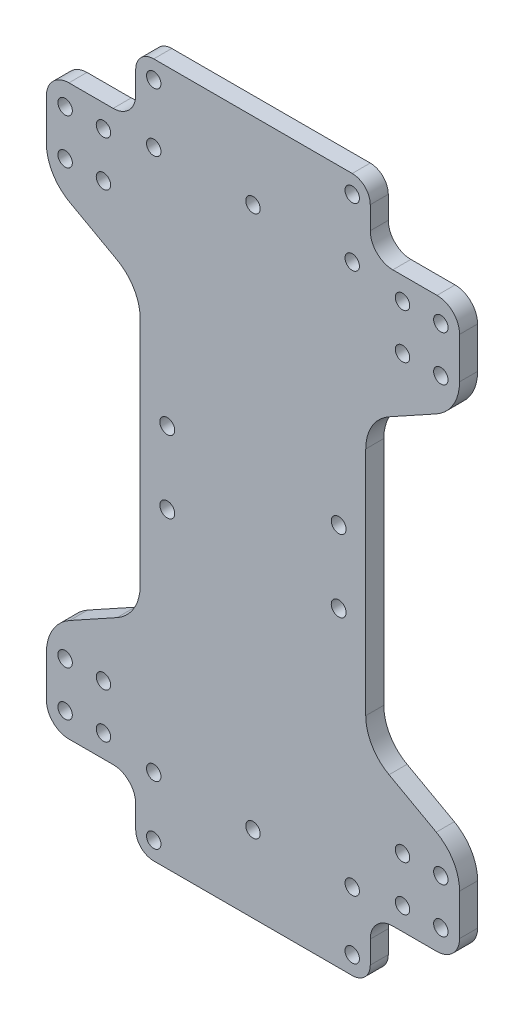
SolidWorks part; units mm, degrees
material "Acrylic (Medium-high impact)"
ref_plane "Front Plane" through (0, 0, 0) normal (0, 0, 1) x (1, 0, 0)
ref_plane "Top Plane" through (0, 0, 0) normal (0, 1, 0) x (1, 0, 0)
ref_plane "Right Plane" through (0, 0, 0) normal (1, 0, 0) x (0, 0, -1)
sketch "Sketch1" plane through (0, 0, 0) normal (0, 0, 1) x (1, 0, 0)
  line L0 (1.25, 62.9364) -> (93.1655, 62.9364) construction
  line L1 (1.4077, -0.0636) -> (16.2069, -0.0636)
  line L2 (1.4077, -0.0636) -> (1.4077, 19.9364)
  line L3 (69.2085, 2.9364) -> (69.2085, -10.0636) construction
  line L4 (80.3577, 4.9364) -> (80.3577, 14.9364) construction
  line L5 (1.4077, 19.9364) -> (22.2077, 31.43)
  line L6 (25.2069, 2.9364) -> (47.2077, 2.9364) construction
  line L7 (88.8577, 14.9364) -> (80.3577, 14.9364) construction
  line L8 (47.2077, -14.0636) -> (47.2077, 139.9364) construction
  line L9 (88.8577, 4.9364) -> (88.8577, 14.9364) construction
  line L10 (21.2069, -5.0636) -> (21.2069, -10.0636)
  line L11 (22.2077, 94.4428) -> (22.2077, 31.43)
  line L12 (88.8577, 4.9364) -> (80.3577, 4.9364) construction
  line L13 (80.3577, 9.9364) -> (88.8577, 9.9364) construction
  line L14 (14.0577, 9.9364) -> (5.5577, 9.9364) construction
  line L15 (5.5577, 4.9364) -> (14.0577, 4.9364) construction
  line L16 (5.5577, 4.9364) -> (5.5577, 14.9364) construction
  line L17 (5.5577, 14.9364) -> (14.0577, 14.9364) construction
  line L18 (14.0577, 4.9364) -> (14.0577, 14.9364) construction
  line L19 (72.2077, 94.4428) -> (72.2077, 31.43)
  line L20 (73.2085, -5.0636) -> (73.2085, -10.0636)
  line L21 (93.0077, 19.9364) -> (72.2077, 31.43)
  line L22 (93.0077, -0.0636) -> (93.0077, 19.9364)
  line L23 (93.0077, -0.0636) -> (78.2085, -0.0636)
  line L24 (25.2069, 122.9364) -> (25.2069, 135.9364) construction
  line L25 (14.0577, 120.9364) -> (14.0577, 110.9364) construction
  line L26 (5.5577, 110.9364) -> (14.0577, 110.9364) construction
  line L27 (5.5577, 120.9364) -> (5.5577, 110.9364) construction
  line L28 (5.5577, 120.9364) -> (14.0577, 120.9364) construction
  line L29 (14.0577, 115.9364) -> (5.5577, 115.9364) construction
  line L30 (80.3577, 115.9364) -> (88.8577, 115.9364) construction
  line L31 (88.8577, 120.9364) -> (80.3577, 120.9364) construction
  line L32 (88.8577, 120.9364) -> (88.8577, 110.9364) construction
  line L33 (88.8577, 110.9364) -> (80.3577, 110.9364) construction
  line L34 (25.2069, 122.9364) -> (47.2077, 122.9364) construction
  line L35 (25.2069, -14.0636) -> (69.2085, -14.0636)
  line L36 (80.3577, 120.9364) -> (80.3577, 110.9364) construction
  line L37 (69.2085, 122.9364) -> (69.2085, 135.9364) construction
  line L38 (25.2069, 2.9364) -> (25.2069, -10.0636) construction
  line L39 (25.2069, 139.9364) -> (69.2085, 139.9364)
  line L40 (93.0077, 125.9364) -> (78.2085, 125.9364)
  line L41 (93.0077, 125.9364) -> (93.0077, 105.9364)
  line L42 (93.0077, 105.9364) -> (72.2077, 94.4428)
  line L43 (73.2085, 130.9364) -> (73.2085, 135.9364)
  line L44 (21.2069, 130.9364) -> (21.2069, 135.9364)
  line L45 (1.4077, 105.9364) -> (22.2077, 94.4428)
  line L46 (1.4077, 125.9364) -> (1.4077, 105.9364)
  line L47 (1.4077, 125.9364) -> (16.2069, 125.9364)
  circle A0 centre (5.5577, 4.9364) radius 1.6
  circle A1 centre (14.0577, 4.9364) radius 1.6
  circle A2 centre (14.0577, 14.9364) radius 1.6
  circle A3 centre (5.5577, 14.9364) radius 1.6
  arc A4 (69.2085, -14.0636) -> (73.2085, -10.0636) centre (69.2085, -10.0636) ccw
  arc A5 (73.2085, -5.0636) -> (78.2085, -0.0636) centre (78.2085, -5.0636) cw
  circle A6 centre (69.2085, -10.0636) radius 1.6
  circle A7 centre (69.2085, 2.9364) radius 1.6
  circle A8 centre (47.2069, 2.9364) radius 1.6
  circle A9 centre (66.2077, 54.9364) radius 1.65
  circle A10 centre (88.8577, 14.9364) radius 1.6
  circle A11 centre (80.3577, 14.9364) radius 1.6
  circle A12 centre (80.3577, 4.9364) radius 1.6
  circle A13 centre (88.8577, 4.9364) radius 1.6
  arc A14 (25.2069, 139.9364) -> (21.2069, 135.9364) centre (25.2069, 135.9364) ccw
  arc A15 (21.2069, 130.9364) -> (16.2069, 125.9364) centre (16.2069, 130.9364) cw
  circle A16 centre (28.2077, 54.9364) radius 1.65
  circle A17 centre (25.2069, 135.9364) radius 1.6
  circle A18 centre (25.2069, 2.9364) radius 1.6
  circle A19 centre (25.2069, 122.9364) radius 1.6
  circle A20 centre (28.2077, 70.9364) radius 1.65
  circle A21 centre (25.2069, -10.0636) radius 1.6
  circle A22 centre (88.8577, 120.9364) radius 1.6
  arc A23 (21.2069, -5.0636) -> (16.2069, -0.0636) centre (16.2069, -5.0636) ccw
  arc A24 (25.2069, -14.0636) -> (21.2069, -10.0636) centre (25.2069, -10.0636) cw
  circle A25 centre (80.3577, 120.9364) radius 1.6
  circle A26 centre (80.3577, 110.9364) radius 1.6
  circle A27 centre (88.8577, 110.9364) radius 1.6
  circle A28 centre (66.2077, 70.9364) radius 1.65
  circle A29 centre (47.2069, 122.9364) radius 1.6
  circle A30 centre (69.2085, 122.9364) radius 1.6
  circle A31 centre (69.2085, 135.9364) radius 1.6
  arc A32 (73.2085, 130.9364) -> (78.2085, 125.9364) centre (78.2085, 130.9364) ccw
  arc A33 (69.2085, 139.9364) -> (73.2085, 135.9364) centre (69.2085, 135.9364) cw
  circle A34 centre (5.5577, 110.9364) radius 1.6
  circle A35 centre (14.0577, 110.9364) radius 1.6
  circle A36 centre (14.0577, 120.9364) radius 1.6
  circle A37 centre (5.5577, 120.9364) radius 1.6
  point P3 (0, 0)
  point P61 (47.2077, 62.9364)
  point P108 (72.2077, 62.9364)
  point P109 (22.2077, 62.9364)
  dimension "D10" = 3.2
  dimension "D15" = 3.2
  dimension "D5" = 45.8
  dimension "D32" = 5
  dimension "D1" = 63
  dimension "D2" = 19
  dimension "D3" = 20
  dimension "D4" = 8
  dimension "D6" = 10
  dimension "D7" = 8.5
  dimension "D8" = 53
  dimension "D9" = 4.15
  dimension "D11" = 13
  dimension "D12" = 7
  dimension "D13" = 22
  dimension "D14" = 25
  dimension "D30" = 14
extrude "Boss-Extrude1" add sketch "Sketch1" along normal blind 4
fillet "Fillet2" radius 10 8 edges at (1.4077, 19.9364, 2) (22.2077, 31.43, 2) (93.0077, 19.9364, 2) (72.2077, 31.43, 2) (93.0077, 105.9364, 2) (72.2077, 94.4428, 2) (1.4077, 105.9364, 2) (22.2077, 94.4428, 2)
fillet "Fillet3" radius 5 4 edges at (1.4077, -0.0636, 2) (1.4077, 125.9364, 2) (93.0077, 125.9364, 2) (93.0077, -0.0636, 2)
